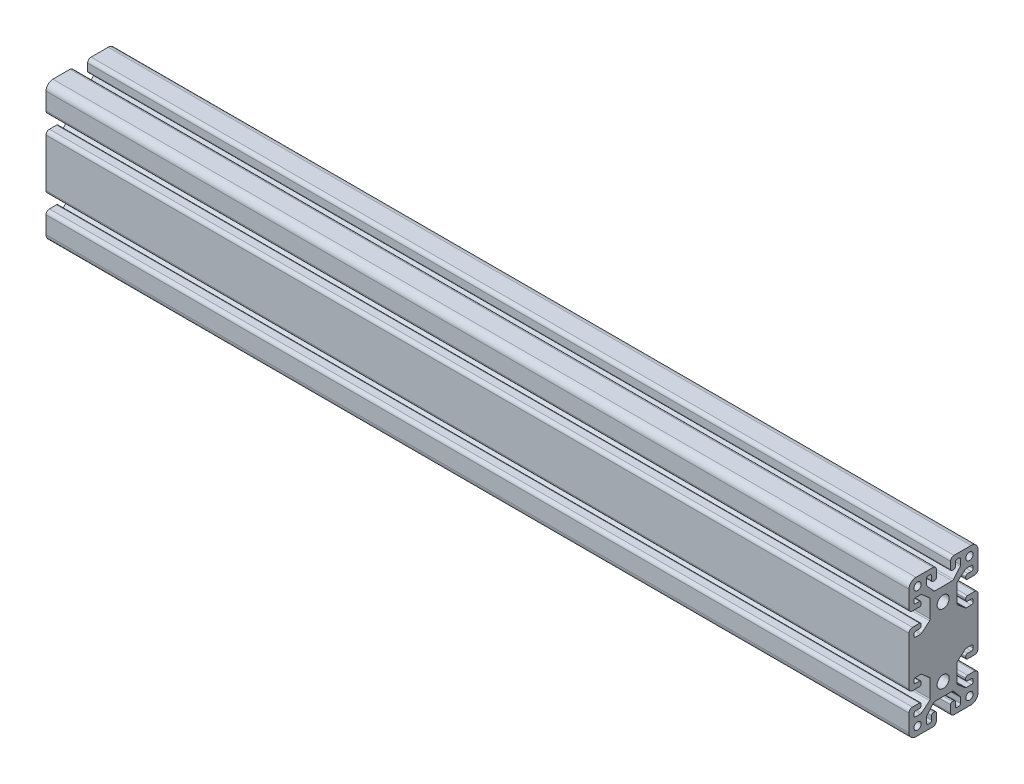
SolidWorks part; units mm, degrees
ref_plane "Alzado" through (0, 0, 0) normal (0, 0, 1) x (1, 0, 0)
ref_plane "Planta" through (0, 0, 0) normal (0, 1, 0) x (1, 0, 0)
ref_plane "Vista lateral" through (0, 0, 0) normal (1, 0, 0) x (0, 0, -1)
sketch "Sketch1" plane through (0, 0, 0) normal (0, 0, 1) x (1, 0, 0)
  line L0 (0, 0) -> (500, 0)
  dimension "D1" = 500
other "Perfil80x40 80X40(1)"
ref_plane "Plane1" through (0, 0, 0) normal (1, 0, 0) x (0, 1, 0)
sketch "Sketch9" plane through (0, 0, 0) normal (1, 0, 0) x (0, 1, 0)
  line L0 (10.3366, -12.8114) -> (14.2004, -8.2451)
  line L1 (14.9638, -7.891) -> (25.0362, -7.891)
  line L2 (25.7996, -8.2451) -> (29.6634, -12.8114)
  line L3 (29.9, -13.4573) -> (29.9, -16.391)
  line L4 (28.9, -17.391) -> (27.9, -17.391)
  line L5 (26.9, -16.391) -> (26.9, -14.091)
  line L6 (25.9, -13.091) -> (25.1, -13.091)
  line L7 (24.1, -14.091) -> (24.1, -18.191)
  line L8 (26.1, -20.191) -> (36, -20.191)
  line L9 (40, -16.191) -> (40, -6.291)
  line L10 (38, -4.291) -> (33.9, -4.291)
  line L11 (32.9, -5.291) -> (32.9, -6.091)
  line L12 (33.9, -7.091) -> (36.2, -7.091)
  line L13 (37.2, -8.091) -> (37.2, -9.091)
  line L14 (36.2, -10.091) -> (33.2663, -10.091)
  line L15 (32.6204, -9.8544) -> (28.0541, -5.9906)
  line L16 (27.7, -5.2272) -> (27.7, 4.8452)
  line L17 (28.0541, 5.6086) -> (32.6204, 9.4724)
  line L18 (33.2663, 9.709) -> (36.2, 9.709)
  line L19 (37.2, 8.709) -> (37.2, 7.709)
  line L20 (36.2, 6.709) -> (33.9, 6.709)
  line L21 (32.9, 5.709) -> (32.9, 4.909)
  line L22 (33.9, 3.909) -> (38, 3.909)
  line L23 (40, 5.909) -> (40, 15.809)
  line L24 (36, 19.809) -> (26.1, 19.809)
  line L25 (24.1, 17.809) -> (24.1, 13.709)
  line L26 (25.1, 12.709) -> (25.9, 12.709)
  line L27 (26.9, 13.709) -> (26.9, 16.009)
  line L28 (27.9, 17.009) -> (28.9, 17.009)
  line L29 (29.9, 16.009) -> (29.9, 13.0753)
  line L30 (29.6634, 12.4294) -> (25.7996, 7.863)
  line L31 (25.0362, 7.509) -> (14.9638, 7.509)
  line L32 (14.2004, 7.863) -> (10.3366, 12.4294)
  line L33 (10.1, 13.0753) -> (10.1, 16.009)
  line L34 (11.1, 17.009) -> (12.1, 17.009)
  line L35 (13.1, 16.009) -> (13.1, 13.709)
  line L36 (14.1, 12.709) -> (14.9, 12.709)
  line L37 (15.9, 13.709) -> (15.9, 17.809)
  line L38 (13.9, 19.809) -> (-13.9, 19.809)
  line L39 (-15.9, 17.809) -> (-15.9, 13.709)
  line L40 (-14.9, 12.709) -> (-14.1, 12.709)
  line L41 (-13.1, 13.709) -> (-13.1, 16.009)
  line L42 (-12.1, 17.009) -> (-11.1, 17.009)
  line L43 (-10.1, 16.009) -> (-10.1, 13.0753)
  line L44 (-10.3366, 12.4294) -> (-14.2004, 7.863)
  line L45 (-14.9638, 7.509) -> (-25.0362, 7.509)
  line L46 (-25.7996, 7.863) -> (-29.6634, 12.4294)
  line L47 (-29.9, 13.0753) -> (-29.9, 16.009)
  line L48 (-28.9, 17.009) -> (-27.9, 17.009)
  line L49 (-26.9, 16.009) -> (-26.9, 13.709)
  line L50 (-25.9, 12.709) -> (-25.1, 12.709)
  line L51 (-24.1, 13.709) -> (-24.1, 17.809)
  line L52 (-26.1, 19.809) -> (-36, 19.809)
  line L53 (-40, 15.809) -> (-40, 5.909)
  line L54 (-38, 3.909) -> (-33.9, 3.909)
  line L55 (-32.9, 4.909) -> (-32.9, 5.709)
  line L56 (-33.9, 6.709) -> (-36.2, 6.709)
  line L57 (-37.2, 7.709) -> (-37.2, 8.709)
  line L58 (-36.2, 9.709) -> (-33.2663, 9.709)
  line L59 (-32.6204, 9.4724) -> (-28.0541, 5.6086)
  line L60 (-27.7, 4.8452) -> (-27.7, -5.2272)
  line L61 (-28.0541, -5.9906) -> (-32.6204, -9.8544)
  line L62 (-33.2663, -10.091) -> (-36.2, -10.091)
  line L63 (-37.2, -9.091) -> (-37.2, -8.091)
  line L64 (-36.2, -7.091) -> (-33.9, -7.091)
  line L65 (-32.9, -6.091) -> (-32.9, -5.291)
  line L66 (-33.9, -4.291) -> (-38, -4.291)
  line L67 (-40, -6.291) -> (-40, -16.191)
  line L68 (-36, -20.191) -> (-26.1, -20.191)
  line L69 (-24.1, -18.191) -> (-24.1, -14.091)
  line L70 (-25.1, -13.091) -> (-25.9, -13.091)
  line L71 (-26.9, -14.091) -> (-26.9, -16.391)
  line L72 (-27.9, -17.391) -> (-28.9, -17.391)
  line L73 (-29.9, -16.391) -> (-29.9, -13.4573)
  line L74 (-29.6634, -12.8114) -> (-25.7996, -8.2451)
  line L75 (-25.0362, -7.891) -> (-14.9638, -7.891)
  line L76 (-14.2004, -8.2451) -> (-10.3366, -12.8114)
  line L77 (-10.1, -13.4573) -> (-10.1, -16.391)
  line L78 (-11.1, -17.391) -> (-12.1, -17.391)
  line L79 (-13.1, -16.391) -> (-13.1, -14.091)
  line L80 (-14.1, -13.091) -> (-14.9, -13.091)
  line L81 (-15.9, -14.091) -> (-15.9, -18.191)
  line L82 (-13.9, -20.191) -> (13.9, -20.191)
  line L83 (15.9, -18.191) -> (15.9, -14.091)
  line L84 (14.9, -13.091) -> (14.1, -13.091)
  line L85 (13.1, -14.091) -> (13.1, -16.391)
  line L86 (12.1, -17.391) -> (11.1, -17.391)
  line L87 (10.1, -16.391) -> (10.1, -13.4573)
  circle A0 centre (19.8138, 0) radius 3.5
  circle A1 centre (-20.1862, 0) radius 3.5
  circle A2 centre (35.05, -15.241) radius 2.11
  circle A3 centre (35.05, 14.859) radius 2.11
  circle A4 centre (-35.05, 14.859) radius 2.11
  circle A5 centre (-35.05, -15.241) radius 2.11
  arc A6 (10.3366, -12.8114) -> (10.1, -13.4573) centre (11.1, -13.4573) ccw
  arc A7 (14.9638, -7.891) -> (14.2004, -8.2451) centre (14.9638, -8.891) ccw
  arc A8 (25.7996, -8.2451) -> (25.0362, -7.891) centre (25.0362, -8.891) ccw
  arc A9 (29.9, -13.4573) -> (29.6634, -12.8114) centre (28.9, -13.4573) ccw
  arc A10 (28.9, -17.391) -> (29.9, -16.391) centre (28.9, -16.391) ccw
  arc A11 (26.9, -16.391) -> (27.9, -17.391) centre (27.9, -16.391) ccw
  arc A12 (26.9, -14.091) -> (25.9, -13.091) centre (25.9, -14.091) ccw
  arc A13 (25.1, -13.091) -> (24.1, -14.091) centre (25.1, -14.091) ccw
  arc A14 (24.1, -18.191) -> (26.1, -20.191) centre (26.1, -18.191) ccw
  arc A15 (36, -20.191) -> (40, -16.191) centre (36, -16.191) ccw
  arc A16 (40, -6.291) -> (38, -4.291) centre (38, -6.291) ccw
  arc A17 (33.9, -4.291) -> (32.9, -5.291) centre (33.9, -5.291) ccw
  arc A18 (32.9, -6.091) -> (33.9, -7.091) centre (33.9, -6.091) ccw
  arc A19 (37.2, -8.091) -> (36.2, -7.091) centre (36.2, -8.091) ccw
  arc A20 (36.2, -10.091) -> (37.2, -9.091) centre (36.2, -9.091) ccw
  arc A21 (32.6204, -9.8544) -> (33.2663, -10.091) centre (33.2663, -9.091) ccw
  arc A22 (27.7, -5.2272) -> (28.0541, -5.9906) centre (28.7, -5.2272) ccw
  arc A23 (28.0541, 5.6086) -> (27.7, 4.8452) centre (28.7, 4.8452) ccw
  arc A24 (33.2663, 9.709) -> (32.6204, 9.4724) centre (33.2663, 8.709) ccw
  arc A25 (37.2, 8.709) -> (36.2, 9.709) centre (36.2, 8.709) ccw
  arc A26 (36.2, 6.709) -> (37.2, 7.709) centre (36.2, 7.709) ccw
  arc A27 (33.9, 6.709) -> (32.9, 5.709) centre (33.9, 5.709) ccw
  arc A28 (32.9, 4.909) -> (33.9, 3.909) centre (33.9, 4.909) ccw
  arc A29 (38, 3.909) -> (40, 5.909) centre (38, 5.909) ccw
  arc A30 (40, 15.809) -> (36, 19.809) centre (36, 15.809) ccw
  arc A31 (26.1, 19.809) -> (24.1, 17.809) centre (26.1, 17.809) ccw
  arc A32 (24.1, 13.709) -> (25.1, 12.709) centre (25.1, 13.709) ccw
  arc A33 (25.9, 12.709) -> (26.9, 13.709) centre (25.9, 13.709) ccw
  arc A34 (27.9, 17.009) -> (26.9, 16.009) centre (27.9, 16.009) ccw
  arc A35 (29.9, 16.009) -> (28.9, 17.009) centre (28.9, 16.009) ccw
  arc A36 (29.6634, 12.4294) -> (29.9, 13.0753) centre (28.9, 13.0753) ccw
  arc A37 (25.0362, 7.509) -> (25.7996, 7.863) centre (25.0362, 8.509) ccw
  arc A38 (14.2004, 7.863) -> (14.9638, 7.509) centre (14.9638, 8.509) ccw
  arc A39 (10.1, 13.0753) -> (10.3366, 12.4294) centre (11.1, 13.0753) ccw
  arc A40 (11.1, 17.009) -> (10.1, 16.009) centre (11.1, 16.009) ccw
  arc A41 (13.1, 16.009) -> (12.1, 17.009) centre (12.1, 16.009) ccw
  arc A42 (13.1, 13.709) -> (14.1, 12.709) centre (14.1, 13.709) ccw
  arc A43 (14.9, 12.709) -> (15.9, 13.709) centre (14.9, 13.709) ccw
  arc A44 (15.9, 17.809) -> (13.9, 19.809) centre (13.9, 17.809) ccw
  arc A45 (-13.9, 19.809) -> (-15.9, 17.809) centre (-13.9, 17.809) ccw
  arc A46 (-15.9, 13.709) -> (-14.9, 12.709) centre (-14.9, 13.709) ccw
  arc A47 (-14.1, 12.709) -> (-13.1, 13.709) centre (-14.1, 13.709) ccw
  arc A48 (-12.1, 17.009) -> (-13.1, 16.009) centre (-12.1, 16.009) ccw
  arc A49 (-10.1, 16.009) -> (-11.1, 17.009) centre (-11.1, 16.009) ccw
  arc A50 (-10.3366, 12.4294) -> (-10.1, 13.0753) centre (-11.1, 13.0753) ccw
  arc A51 (-14.9638, 7.509) -> (-14.2004, 7.863) centre (-14.9638, 8.509) ccw
  arc A52 (-25.7996, 7.863) -> (-25.0362, 7.509) centre (-25.0362, 8.509) ccw
  arc A53 (-29.9, 13.0753) -> (-29.6634, 12.4294) centre (-28.9, 13.0753) ccw
  arc A54 (-28.9, 17.009) -> (-29.9, 16.009) centre (-28.9, 16.009) ccw
  arc A55 (-26.9, 16.009) -> (-27.9, 17.009) centre (-27.9, 16.009) ccw
  arc A56 (-26.9, 13.709) -> (-25.9, 12.709) centre (-25.9, 13.709) ccw
  arc A57 (-25.1, 12.709) -> (-24.1, 13.709) centre (-25.1, 13.709) ccw
  arc A58 (-24.1, 17.809) -> (-26.1, 19.809) centre (-26.1, 17.809) ccw
  arc A59 (-36, 19.809) -> (-40, 15.809) centre (-36, 15.809) ccw
  arc A60 (-40, 5.909) -> (-38, 3.909) centre (-38, 5.909) ccw
  arc A61 (-33.9, 3.909) -> (-32.9, 4.909) centre (-33.9, 4.909) ccw
  arc A62 (-32.9, 5.709) -> (-33.9, 6.709) centre (-33.9, 5.709) ccw
  arc A63 (-37.2, 7.709) -> (-36.2, 6.709) centre (-36.2, 7.709) ccw
  arc A64 (-36.2, 9.709) -> (-37.2, 8.709) centre (-36.2, 8.709) ccw
  arc A65 (-32.6204, 9.4724) -> (-33.2663, 9.709) centre (-33.2663, 8.709) ccw
  arc A66 (-27.7, 4.8452) -> (-28.0541, 5.6086) centre (-28.7, 4.8452) ccw
  arc A67 (-28.0541, -5.9906) -> (-27.7, -5.2272) centre (-28.7, -5.2272) ccw
  arc A68 (-33.2663, -10.091) -> (-32.6204, -9.8544) centre (-33.2663, -9.091) ccw
  arc A69 (-37.2, -9.091) -> (-36.2, -10.091) centre (-36.2, -9.091) ccw
  arc A70 (-36.2, -7.091) -> (-37.2, -8.091) centre (-36.2, -8.091) ccw
  arc A71 (-33.9, -7.091) -> (-32.9, -6.091) centre (-33.9, -6.091) ccw
  arc A72 (-32.9, -5.291) -> (-33.9, -4.291) centre (-33.9, -5.291) ccw
  arc A73 (-38, -4.291) -> (-40, -6.291) centre (-38, -6.291) ccw
  arc A74 (-40, -16.191) -> (-36, -20.191) centre (-36, -16.191) ccw
  arc A75 (-26.1, -20.191) -> (-24.1, -18.191) centre (-26.1, -18.191) ccw
  arc A76 (-24.1, -14.091) -> (-25.1, -13.091) centre (-25.1, -14.091) ccw
  arc A77 (-25.9, -13.091) -> (-26.9, -14.091) centre (-25.9, -14.091) ccw
  arc A78 (-27.9, -17.391) -> (-26.9, -16.391) centre (-27.9, -16.391) ccw
  arc A79 (-29.9, -16.391) -> (-28.9, -17.391) centre (-28.9, -16.391) ccw
  arc A80 (-29.6634, -12.8114) -> (-29.9, -13.4573) centre (-28.9, -13.4573) ccw
  arc A81 (-25.0362, -7.891) -> (-25.7996, -8.2451) centre (-25.0362, -8.891) ccw
  arc A82 (-14.2004, -8.2451) -> (-14.9638, -7.891) centre (-14.9638, -8.891) ccw
  arc A83 (-10.1, -13.4573) -> (-10.3366, -12.8114) centre (-11.1, -13.4573) ccw
  arc A84 (-11.1, -17.391) -> (-10.1, -16.391) centre (-11.1, -16.391) ccw
  arc A85 (-13.1, -16.391) -> (-12.1, -17.391) centre (-12.1, -16.391) ccw
  arc A86 (-13.1, -14.091) -> (-14.1, -13.091) centre (-14.1, -14.091) ccw
  arc A87 (-14.9, -13.091) -> (-15.9, -14.091) centre (-14.9, -14.091) ccw
  arc A88 (-15.9, -18.191) -> (-13.9, -20.191) centre (-13.9, -18.191) ccw
  arc A89 (13.9, -20.191) -> (15.9, -18.191) centre (13.9, -18.191) ccw
  arc A90 (15.9, -14.091) -> (14.9, -13.091) centre (14.9, -14.091) ccw
  arc A91 (14.1, -13.091) -> (13.1, -14.091) centre (14.1, -14.091) ccw
  arc A92 (12.1, -17.391) -> (13.1, -16.391) centre (12.1, -16.391) ccw
  arc A93 (10.1, -16.391) -> (11.1, -17.391) centre (11.1, -16.391) ccw
  point P276 (0, 0)
  point P277 (-20.1862, 19.809)
  point P278 (-20.1862, -20.191)
  point P279 (-40, 0)
  point P280 (40, 0)
  point P281 (19.8138, 19.809)
  point P282 (0, 19.809)
  point P283 (0, -20.191)
  point P284 (19.8138, -20.191)
  point P285 (-40, -20.191)
  point P286 (-40, 19.809)
  point P287 (40, 19.809)
  point P288 (40, -20.191)
  point P289 (0, 0)
